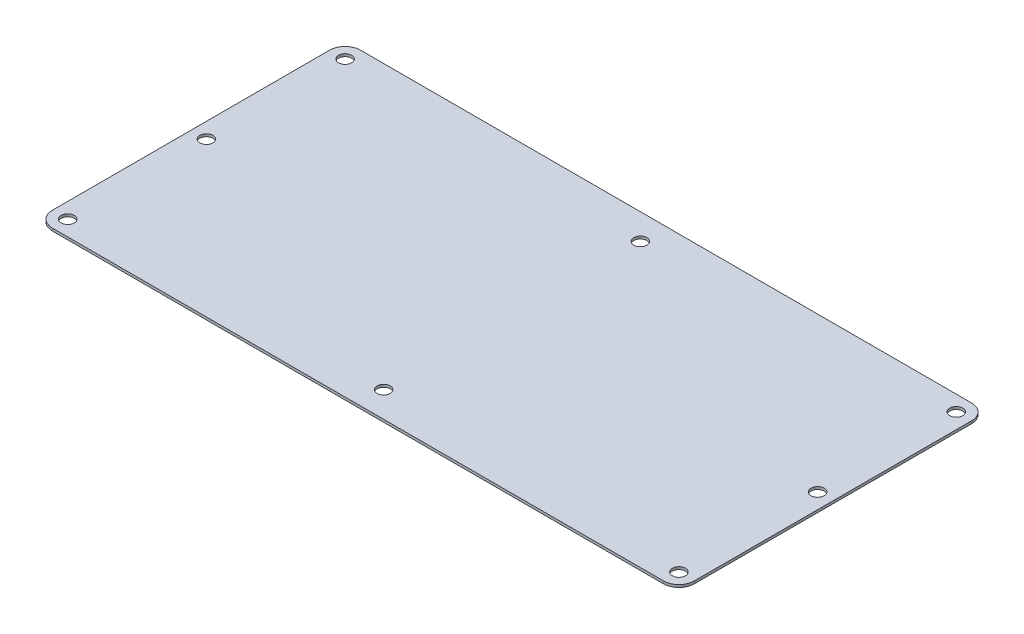
SolidWorks part; units mm, degrees
ref_plane "前视基准面" through (0, 0, 0) normal (0, 0, 1) x (1, 0, 0)
ref_plane "上视基准面" through (0, 0, 0) normal (0, 1, 0) x (1, 0, 0)
ref_plane "右视基准面" through (0, 0, 0) normal (1, 0, 0) x (0, 0, -1)
sketch "草图1" plane through (0, 0, 0) normal (0, 1, 0) x (1, 0, 0)
  line L0 (30.3436, 133.1371) -> (268.3436, 133.1371)
  line L1 (274.3436, 127.1371) -> (274.3436, 19.1371)
  line L2 (268.3436, 13.1371) -> (30.3436, 13.1371)
  line L3 (24.3436, 19.1371) -> (24.3436, 127.1371)
  arc A0 (30.3436, 133.1371) -> (24.3436, 127.1371) centre (30.3436, 127.1371) ccw
  arc A1 (274.3436, 127.1371) -> (268.3436, 133.1371) centre (268.3436, 127.1371) ccw
  arc A2 (268.3436, 13.1371) -> (274.3436, 19.1371) centre (268.3436, 19.1371) ccw
  arc A3 (24.3436, 19.1371) -> (30.3436, 13.1371) centre (30.3436, 19.1371) ccw
  circle A4 centre (30.3436, 127.1371) radius 2.55
  circle A5 centre (268.3436, 127.1371) radius 2.55
  circle A6 centre (149.3436, 123.1371) radius 2.55
  circle A7 centre (30.3436, 19.1371) radius 2.55
  circle A8 centre (268.3436, 19.1371) radius 2.55
  circle A9 centre (149.3436, 23.1371) radius 2.55
  circle A10 centre (268.3436, 73.1371) radius 2.55
  circle A11 centre (30.3436, 73.1371) radius 2.55
extrude "凸台-拉伸1" add sketch "草图1" along normal blind 1
